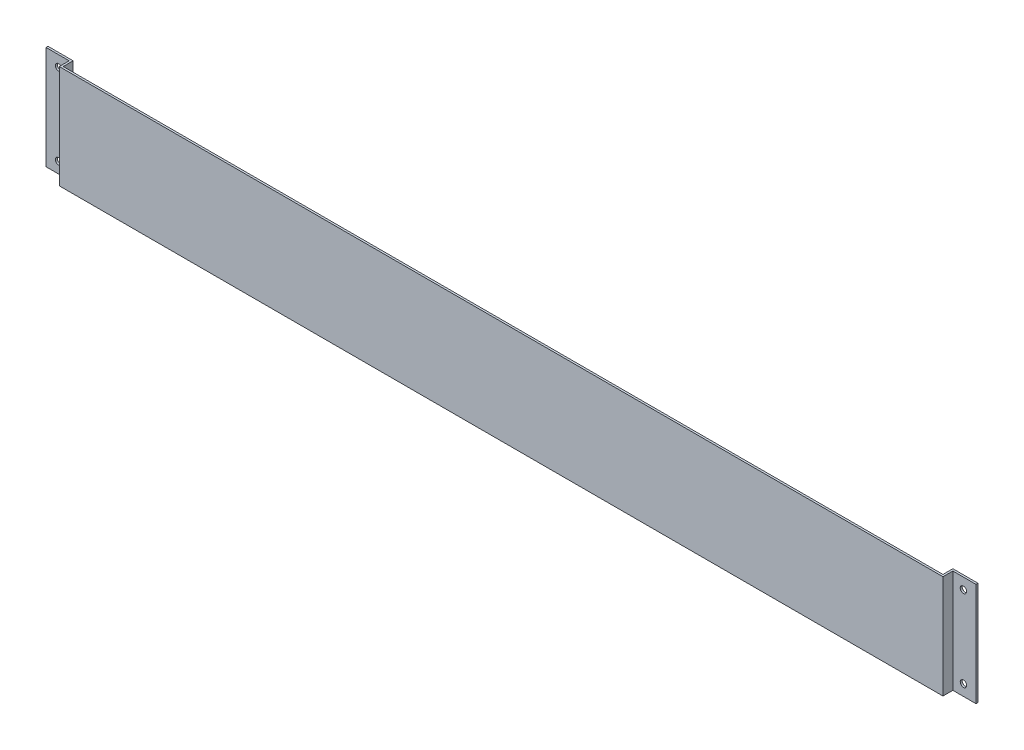
SolidWorks part; units mm, degrees
ref_plane "Front Plane" through (0, 0, 0) normal (0, 0, 1) x (1, 0, 0)
ref_plane "Top Plane" through (0, 0, 0) normal (0, 1, 0) x (1, 0, 0)
ref_plane "Right Plane" through (0, 0, 0) normal (1, 0, 0) x (0, 0, -1)
sketch "Sketch1" plane through (0, 0, 0) normal (0, 1, 0) x (1, 0, 0)
  line L2 (916.4, 30.469) -> (23.4, 30.469)
  line L3 (23.4, 30.469) -> (23.4, 40.469)
  line L4 (23.4, 40.469) -> (0, 40.469)
  line L5 (0, 40.469) -> (0, 42.469)
  line L6 (0, 42.469) -> (25.4, 42.469)
  line L7 (25.4, 42.469) -> (25.4, 32.469)
  line L8 (25.4, 32.469) -> (914.4, 32.469)
  line L12 (914.4, 32.469) -> (914.4, 42.469)
  line L13 (914.4, 42.469) -> (939.8, 42.469)
  line L14 (939.8, 42.469) -> (939.8, 40.469)
  line L15 (939.8, 40.469) -> (916.4, 40.469)
  line L16 (916.4, 40.469) -> (916.4, 30.469)
  dimension "D1" = 2
  dimension "D2" = 2
  dimension "D3" = 10
  dimension "D4" = 2
  dimension "D5" = 25.4
  dimension "D6" = 25.4
  dimension "D7" = 10
  dimension "D8" = 2
  dimension "D9" = 2
  dimension "D10" = 939.8
extrude "Boss-Extrude1" add sketch "Sketch1" along normal blind 104.45
sketch "Sketch2" plane through (0, 0, -40.469) normal (0, 0, 1) x (1, 0, 0)
  line L0 (0, 104.45) -> (0, 0) construction
  line L1 (0, 104.45) -> (23.4, 104.45) construction
  line L2 (916.4, 104.45) -> (939.8, 104.45) construction
  line L3 (939.8, 104.45) -> (939.8, 0) construction
  line L4 (0, 0) -> (23.4, 0) construction
  line L5 (939.8, 0) -> (914.4, 0) construction
  circle A0 centre (927.1, 11.11) radius 3.25
  circle A1 centre (927.1, 93.34) radius 3.25
  circle A2 centre (12.7, 11.11) radius 3.25
  circle A3 centre (12.7, 93.34) radius 3.25
  dimension "D1" = 6.5
  dimension "D2" = 12.7
  dimension "D3" = 11.11
  dimension "D4" = 6.5
  dimension "D5" = 12.7
  dimension "D6" = 11.11
  dimension "D7" = 6.5
  dimension "D8" = 6.5
  dimension "D9" = 11.11
  dimension "D10" = 12.7
  dimension "D11" = 12.7
  dimension "D12" = 11.11
extrude "Cut-Extrude1" cut sketch "Sketch2" against normal through all
